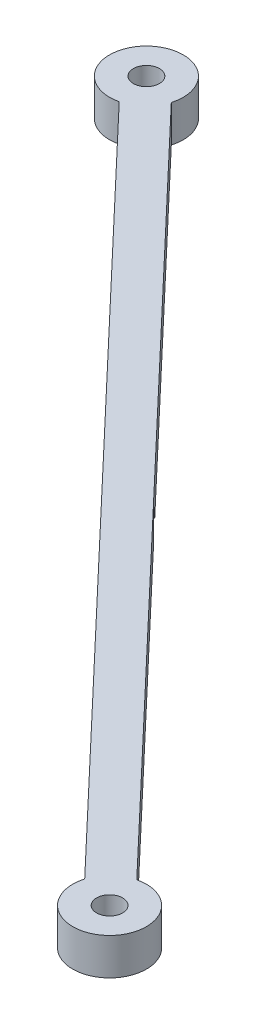
SolidWorks part; units mm, degrees
ref_plane "Front Plane" through (0, 0, 0) normal (0, 0, 1) x (1, 0, 0)
ref_plane "Top Plane" through (0, 0, 0) normal (0, 1, 0) x (1, 0, 0)
ref_plane "Right Plane" through (0, 0, 0) normal (1, 0, 0) x (0, 0, -1)
sketch "Sketch1" plane through (0, 0, 0) normal (0, 1, 0) x (1, 0, 0)
  line L0 (-28.3882, -6.4277) -> (92.2618, -133.4277)
  line L1 (92.2618, -133.4277) -> (94.5637, -131.2409)
  line L2 (94.5637, -131.2409) -> (-26.0863, -4.2409)
  line L3 (89.9599, -135.6144) -> (-30.6901, -8.6144)
  circle A0 centre (-28.3882, -6.4277) radius 2.2479
  circle A1 centre (-28.3882, -6.4277) radius 3.175
  circle A2 centre (-28.3882, -6.4277) radius 6.35
  circle A3 centre (92.2618, -133.4277) radius 2.2479
  circle A4 centre (92.2618, -133.4277) radius 3.175
  circle A5 centre (92.2618, -133.4277) radius 6.35
  dimension "D1" = 4.4958
  dimension "D2" = 6.35
  dimension "D3" = 12.7
  dimension "D4" = 4.4958
  dimension "D5" = 6.35
  dimension "D6" = 12.7
  dimension "D7" = 120.65
  dimension "D8" = 127
extrude "Boss-Extrude1" add sketch "Sketch1" along normal blind 6.35
sketch "Sketch2" plane through (0, 0, 0) normal (0, -1, 0) x (1, 0, 0)
  line L0 (31.9274, 65.308) -> (27.5641, 69.9347)
  line L1 (90.7761, 127.2539) -> (-22.2987, 8.2278) construction
  line L2 (86.1856, 8.2278) -> (-26.8892, 127.2539) construction
  line L3 (86.1723, 131.6275) -> (-26.9025, 12.6014) construction
  line L4 (27.5641, 69.9347) -> (31.8546, 74.638)
  line L5 (90.7894, 12.6014) -> (-22.2854, 131.6275) construction
  line L6 (31.8546, 74.638) -> (36.3228, 69.9347)
  line L7 (36.3228, 69.9347) -> (31.9274, 65.308)
extrude "Cut-Extrude1" cut sketch "Sketch2" against normal blind 3.175
